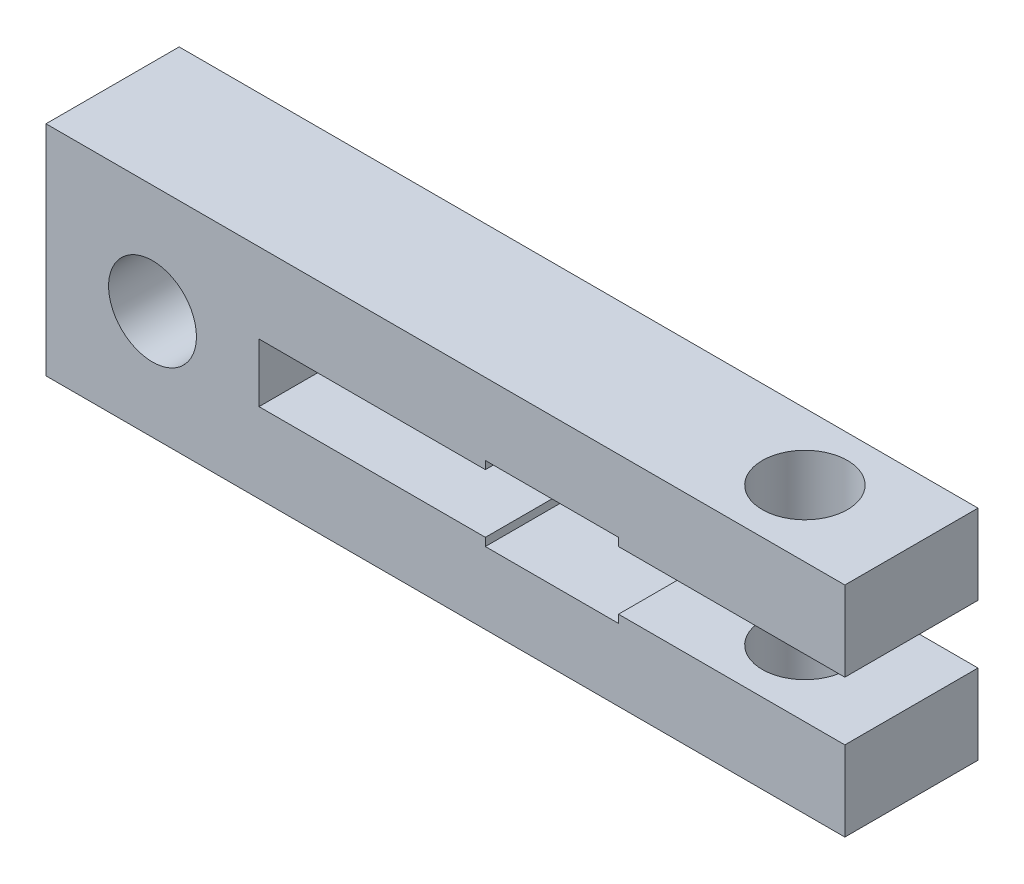
SolidWorks part; units mm, degrees
ref_plane "前视基准面" through (0, 0, 0) normal (0, 0, 1) x (1, 0, 0)
ref_plane "上视基准面" through (0, 0, 0) normal (0, 1, 0) x (1, 0, 0)
ref_plane "右视基准面" through (0, 0, 0) normal (1, 0, 0) x (0, 0, -1)
sketch "草图1" plane through (0, 0, 0) normal (0, 0, 1) x (1, 0, 0)
  line L0 (16.5, 0) -> (-16.5, 0) construction
  line L2 (-15, 1.1) -> (15, 1.1)
  line L3 (-15, 1.1) -> (-15, 4.1)
  line L4 (-15, 4.1) -> (15, 4.1)
  line L5 (15, 1.1) -> (15, 4.1)
  line L6 (-15, 1.1) -> (15, 4.1) construction
  line L7 (-15, 4.1) -> (15, 1.1) construction
  line L8 (-15, -4.1) -> (15, -4.1)
  line L9 (15, -1.1) -> (15, -4.1)
  line L10 (-15, -1.1) -> (15, -1.1)
  line L11 (-15, -1.1) -> (-15, -4.1)
  line L12 (-15, -4.1) -> (15, -1.1) construction
  line L13 (-15, -1.1) -> (15, -4.1) construction
  line L14 (-15, 1.1) -> (-7, 1.1)
  line L15 (-15, 1.1) -> (-15, -1.1)
  line L16 (-15, -1.1) -> (-7, -1.1)
  line L17 (-7, 1.1) -> (-7, -1.1)
  point P0 (0, 2.6)
  point P12 (0, -2.6)
  dimension "D1" = 2.2
  dimension "D2" = 3
  dimension "D3" = 30
  dimension "D4" = 8
extrude "凸台-拉伸2" add sketch "草图1" along normal mid plane 5 contours L2 L5 L4 L3 | L17 L2 L15 L10 | L10 L11 L8 L9
sketch "草图2" plane through (0, 0, 2.5) normal (0, 0, 1) x (1, 0, 0)
  circle A0 centre (-11, 0) radius 1.65
  dimension "D1" = 3.3
  dimension "D2" = 11
extrude "切除-拉伸1" cut sketch "草图2" against normal blind 14
sketch "草图3" plane through (0, 0, 2.5) normal (0, 0, 1) x (1, 0, 0)
  line L1 (1.5, -1.4) -> (6.5, -1.4)
  line L2 (1.5, -1.4) -> (1.5, 1.4)
  line L3 (1.5, 1.4) -> (6.5, 1.4)
  line L4 (6.5, -1.4) -> (6.5, 1.4)
  line L5 (1.5, -1.4) -> (6.5, 1.4) construction
  line L6 (1.5, 1.4) -> (6.5, -1.4) construction
  circle A1 centre (-11, 0) radius 1.65 construction
  point P0 (4, 0)
  dimension "D1" = 2.8
  dimension "D2" = 15
  dimension "D3" = 5
extrude "切除-拉伸2" cut sketch "草图3" against normal blind 14
sketch "草图5" plane through (0, 4.1, 0) normal (0, 1, 0) x (1, 0, 0)
  circle A0 centre (11, 0) radius 1.6
  dimension "D1" = 3.2
  dimension "D2" = 11
extrude "切除-拉伸3" cut sketch "草图5" against normal blind 50
